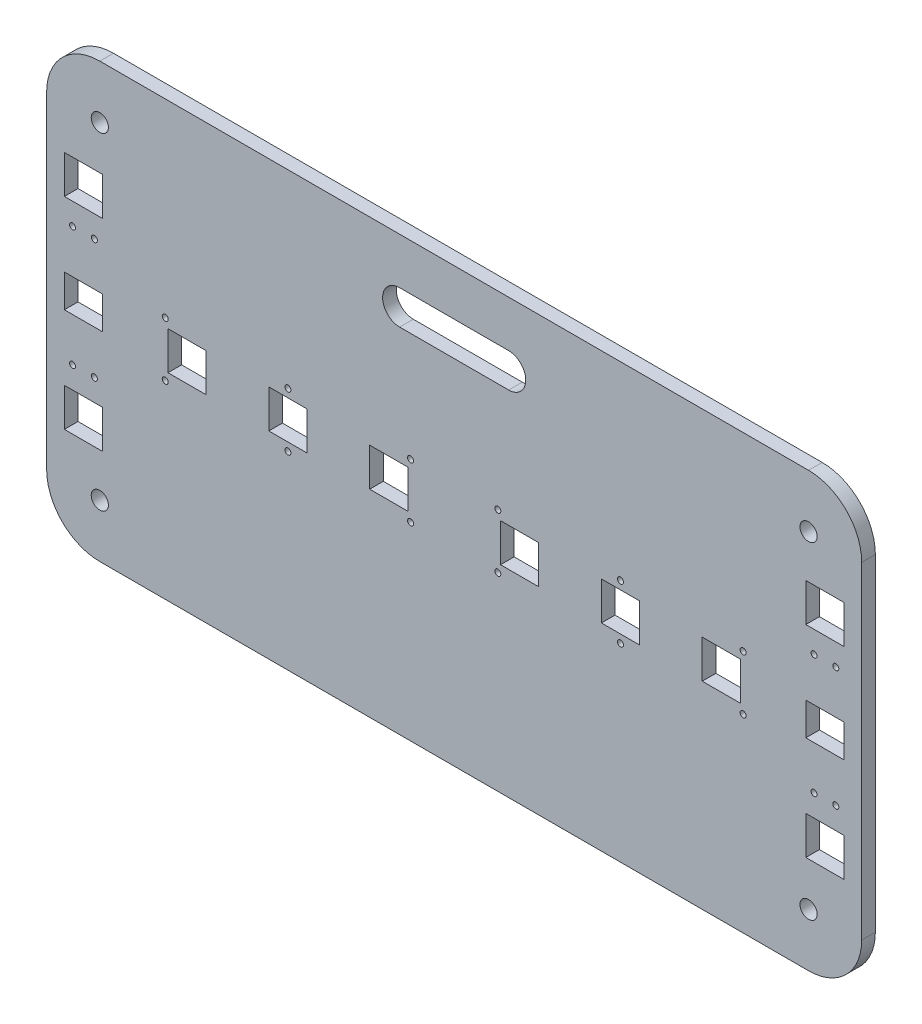
SolidWorks part; units mm, degrees
material "玻璃"
ref_plane "前视基准面" through (0, 0, 0) normal (0, 0, 1) x (1, 0, 0)
ref_plane "上视基准面" through (0, 0, 0) normal (0, 1, 0) x (1, 0, 0)
ref_plane "右视基准面" through (0, 0, 0) normal (1, 0, 0) x (0, 0, -1)
sketch "草图2" plane through (0, 0, 0) normal (0, 0, 1) x (1, 0, 0)
  line L0 (0, 1004.6496) -> (0, 0) construction
  line L10 (-68, -43) -> (-68, -57)
  line L11 (-31, -43) -> (-17, -43)
  line L19 (-22.1829, -50) -> (7.7078, -50) construction
  line L24 (31, -57) -> (17, -57)
  line L29 (17, -43) -> (17, -57)
  line L46 (129, -80) -> (143, -80)
  line L47 (-130, -130) -> (130, -130) construction
  line L48 (-150, -110) -> (-150, 10) construction
  line L49 (-130, 30) -> (130, 30) construction
  line L50 (150, -110) -> (150, 10) construction
  line L51 (0, 30) -> (0, 0) construction
  line L52 (-150, -50) -> (150, -50) construction
  line L53 (129, -6) -> (143, -6)
  line L58 (129, -6) -> (129, -20)
  line L59 (129, -20) -> (143, -20)
  line L60 (143, -6) -> (143, -20)
  line L65 (28.2222, 0) -> (37.5982, 0) construction
  line L66 (0, 0) -> (0, -130) construction
  line L71 (-130, 29.5) -> (130, 29.5)
  line L72 (-20, 12.5) -> (20, 12.5)
  line L73 (0, 0) -> (0, -1009.2088) construction
  line L74 (136, -20) -> (136, -6) construction
  line L75 (129, -13) -> (143, -13) construction
  line L76 (143, -94) -> (143, -80)
  line L77 (129, -94) -> (143, -94)
  line L78 (129, -94) -> (129, -80)
  line L79 (-129, -94) -> (-129, -80)
  line L80 (-129, -94) -> (-143, -94)
  line L81 (-143, -94) -> (-143, -80)
  line L82 (-129, -80) -> (-143, -80)
  line L83 (-129, -20) -> (-143, -20)
  line L84 (-143, -6) -> (-143, -20)
  line L85 (-129, -6) -> (-143, -6)
  line L86 (-129, -6) -> (-129, -20)
  line L87 (-31, -43) -> (-31, -57)
  line L88 (-31, -57) -> (-17, -57)
  line L89 (-17, -43) -> (-17, -57)
  line L90 (-24, -57) -> (-24, -43) construction
  line L91 (-31, -50) -> (-17, -50) construction
  line L92 (-68, -43) -> (-54, -43)
  line L93 (-54, -43) -> (-54, -57)
  line L94 (-68, -57) -> (-54, -57)
  line L95 (-105, -43) -> (-105, -57)
  line L96 (-105, -43) -> (-91, -43)
  line L97 (-91, -43) -> (-91, -57)
  line L98 (-105, -57) -> (-91, -57)
  line L99 (31, -43) -> (17, -43)
  line L100 (31, -43) -> (31, -57)
  line L101 (68, -43) -> (54, -43)
  line L102 (54, -43) -> (54, -57)
  line L103 (68, -57) -> (54, -57)
  line L104 (68, -43) -> (68, -57)
  line L105 (105, -43) -> (91, -43)
  line L106 (91, -43) -> (91, -57)
  line L107 (105, -57) -> (91, -57)
  line L108 (105, -43) -> (105, -57)
  line L109 (-31, -43) -> (-68, -43) construction
  line L110 (-61, -43) -> (-61, -57) construction
  line L112 (-111, -35) -> (-11, -35) construction
  line L113 (-111, -35) -> (-111, -65) construction
  line L114 (-111, -65) -> (-11, -65) construction
  line L115 (-11, -35) -> (-11, -65) construction
  line L116 (-61, -65) -> (-61, -35) construction
  line L117 (-111, -50) -> (-11, -50) construction
  line L121 (-106, -40) -> (-16, -40) construction
  line L122 (-16, -40) -> (-16, -60) construction
  line L123 (-106, -60) -> (-16, -60) construction
  line L124 (-106, -40) -> (-106, -60) construction
  line L125 (136, -20) -> (136, -42.3074) construction
  line L126 (-20, 12.5) -> (-20, 0) construction
  line L127 (128, -4) -> (144, -4) construction
  line L128 (128, -4) -> (128, -96) construction
  line L129 (128, -96) -> (144, -96) construction
  line L130 (144, -4) -> (144, -96) construction
  line L131 (136, -96) -> (136, -4) construction
  line L132 (128, -50) -> (144, -50) construction
  line L133 (132, -28) -> (140, -28) construction
  line L134 (132, -28) -> (132, -72) construction
  line L135 (132, -72) -> (140, -72) construction
  line L136 (140, -28) -> (140, -72) construction
  line L137 (136, -72) -> (136, -28) construction
  line L138 (132, -50) -> (140, -50) construction
  line L139 (-20, 0) -> (20, 0)
  line L140 (20, 12.5) -> (20, 0) construction
  line L141 (0, 0) -> (0, 12.5) construction
  line L142 (-20, 6.25) -> (20, 6.25) construction
  line L143 (149.5, -110) -> (149.5, 10)
  line L144 (-130, -129.5) -> (130, -129.5)
  line L145 (-149.5, -110) -> (-149.5, 10)
  line L146 (-129, -56) -> (-143, -56)
  line L147 (129, -44) -> (143, -44)
  line L148 (129, -44) -> (129, -56)
  line L149 (129, -56) -> (143, -56)
  line L150 (143, -44) -> (143, -56)
  line L151 (136, -56) -> (136, -44) construction
  line L152 (129, -50) -> (143, -50) construction
  line L153 (-143, -44) -> (-143, -56)
  line L154 (-129, -44) -> (-143, -44)
  line L155 (-129, -44) -> (-129, -56)
  arc A0 (130, 30) -> (150, 10) centre (130, 10) cw construction
  arc A1 (150, -110) -> (130, -130) centre (130, -110) cw construction
  arc A2 (-130, -130) -> (-150, -110) centre (-130, -110) cw construction
  arc A3 (-150, 10) -> (-130, 30) centre (-130, 10) cw construction
  circle A5 centre (130, -110) radius 3.15
  circle A6 centre (130, 10) radius 3.15
  circle A7 centre (-130, -110) radius 3.15
  circle A8 centre (-130, 10) radius 3.15
  circle A13 centre (-106, -40) radius 1.1
  circle A14 centre (-106, -60) radius 1.1
  circle A15 centre (-16, -40) radius 1.1
  circle A16 centre (-16, -60) radius 1.1
  circle A17 centre (-61, -60) radius 1.1
  circle A18 centre (-61, -40) radius 1.1
  circle A19 centre (16, -60) radius 1.1
  circle A20 centre (16, -40) radius 1.1
  circle A21 centre (61, -60) radius 1.1
  circle A22 centre (61, -40) radius 1.1
  circle A23 centre (106, -60) radius 1.1
  circle A24 centre (106, -40) radius 1.1
  circle A25 centre (140, -28) radius 1.1
  circle A26 centre (132, -28) radius 1.1
  circle A27 centre (132, -72) radius 1.1
  circle A28 centre (140, -72) radius 1.1
  circle A29 centre (-140, -72) radius 1.1
  circle A30 centre (-132, -72) radius 1.1
  circle A31 centre (-132, -28) radius 1.1
  circle A32 centre (-140, -28) radius 1.1
  arc A33 (-20, 12.5) -> (-20, 0) centre (-20, 6.25) ccw
  arc A34 (20, 0) -> (20, 12.5) centre (20, 6.25) ccw
  arc A35 (130, 29.5) -> (149.5, 10) centre (130, 10) cw
  arc A36 (149.5, -110) -> (130, -129.5) centre (130, -110) cw
  arc A37 (-130, -129.5) -> (-149.5, -110) centre (-130, -110) cw
  arc A38 (-149.5, 10) -> (-130, 29.5) centre (-130, 10) cw
  point P0 (0, 0)
  point P1 (0, 0)
  point P4 (-24, -50)
  point P36 (-61, -50)
  point P38 (0, -50)
  point P39 (-61, -50)
  point P40 (0, -50)
  point P41 (136, -13)
  point P51 (136, -50)
  point P53 (136, -50)
  point P54 (136, -50)
  point P61 (150, 30)
  point P64 (150, -130)
  point P70 (-150, 30)
  point P102 (-61, -40)
  point P103 (-61, -60)
  point P142 (136, -50)
  point P145 (0, 6.25)
  dimension "D15" = 20
  dimension "D16" = 6.3
  dimension "D17" = 6.3
  dimension "D18" = 6.3
  dimension "D19" = 6.3
  dimension "D20" = 30
  dimension "D25" = 2.2
  dimension "D26" = 2.2
  dimension "D27" = 2.2
  dimension "D28" = 2.2
  dimension "D29" = 2.2
  dimension "D30" = 2.2
  dimension "D35" = 2.2
  dimension "D36" = 2.2
  dimension "D37" = 2.2
  dimension "D38" = 2.2
  dimension "D3" = 14
  dimension "D4" = 14
  dimension "D5" = 17
  dimension "D6" = 40
  dimension "D7" = 12.5
  dimension "D8" = 3
  dimension "D9" = 37
  dimension "D10" = 300
  dimension "D11" = 160
  dimension "D12" = 14
  dimension "D13" = 14
  dimension "D14" = 7
  dimension "D21" = 100
  dimension "D22" = 50
  dimension "D23" = 30
  dimension "D24" = 5
  dimension "D31" = 92
  dimension "D32" = 16
  dimension "D33" = 8
  dimension "D34" = 44
  dimension "D39" = 0
  dimension "D41" = 14
  dimension "D42" = 12
  dimension "D40" = 0.5
extrude "凸台-拉伸1" add sketch "草图2" along normal blind 5
